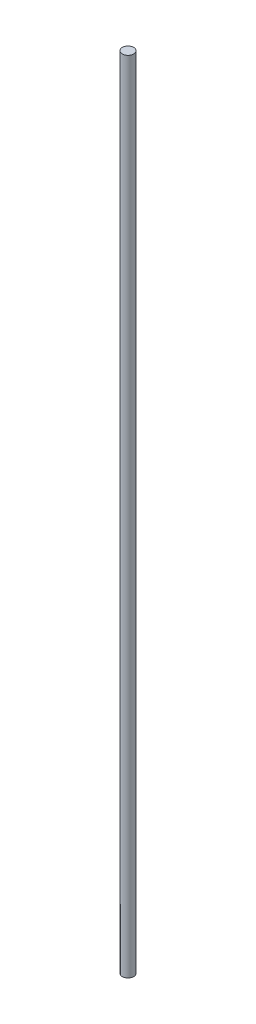
SolidWorks part; units mm, degrees
ref_plane "前视基准面" through (0, 0, 0) normal (0, 0, 1) x (1, 0, 0)
ref_plane "上视基准面" through (0, 0, 0) normal (0, 1, 0) x (1, 0, 0)
ref_plane "右视基准面" through (0, 0, 0) normal (1, 0, 0) x (0, 0, -1)
sketch "草图1" plane through (0, 0, 0) normal (0, 1, 0) x (1, 0, 0)
  circle A0 centre (0, 0) radius 2.5
  dimension "D1" = 5
extrude "凸台-拉伸1" add sketch "草图1" along normal blind 350
